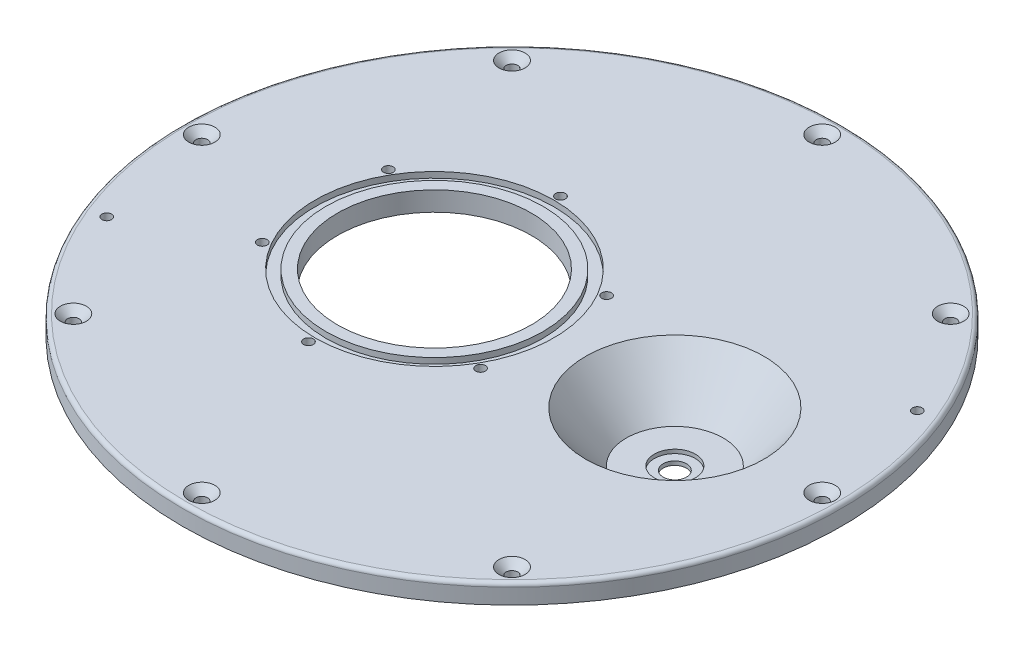
SolidWorks part; units mm, degrees
ref_plane "前视基准面" through (0, 0, 0) normal (0, 0, 1) x (1, 0, 0)
ref_plane "上视基准面" through (0, 0, 0) normal (0, 1, 0) x (1, 0, 0)
ref_plane "右视基准面" through (0, 0, 0) normal (1, 0, 0) x (0, 0, -1)
sketch "草图1" plane through (0, 0, 0) normal (0, 1, 0) x (1, 0, 0)
  circle A0 centre (0, 0) radius 85
  dimension "D1" = 170
extrude "凸台-拉伸1" add sketch "草图1" along normal blind 5
sketch "草图2" plane through (0, 5, 0) normal (0, 1, 0) x (1, 0, 0)
  circle A0 centre (0, 0) radius 80
  circle A1 centre (0, 80) radius 1.25
  circle A2 centre (0, 0) radius 80
  circle A3 centre (56.5685, 56.5685) radius 1.25
  circle A4 centre (0, 0) radius 80
  circle A5 centre (80, 0) radius 1.25
  circle A6 centre (0, 0) radius 80
  circle A7 centre (56.5685, -56.5685) radius 1.25
  circle A8 centre (0, 0) radius 80
  circle A9 centre (0, -80) radius 1.25
  circle A10 centre (0, 0) radius 80
  circle A11 centre (-56.5685, -56.5685) radius 1.25
  circle A12 centre (0, 0) radius 80
  circle A13 centre (-80, 0) radius 1.25
  circle A14 centre (0, 0) radius 80
  circle A15 centre (-56.5685, 56.5685) radius 1.25
  point P28 (0, 0)
  dimension "D1" = 160
  dimension "D2" = 2.5
  dimension "D3" = 8
hole_wizard "M3 螺纹孔1" positions "3D草图2" profile "草图17" tap size "M3" standard "ISO" end condition through all
sketch3d "3D草图2"
  point P0 (0, 5, -80)
  point P3 (56.5685, 5, -56.5685)
  point P6 (80, 5, 0)
  point P9 (56.5685, 5, 56.5685)
  point P12 (0, 5, 80)
  point P15 (-56.5685, 5, 56.5685)
  point P18 (-56.5685, 5, -56.5685)
  point P21 (-80, 5, 0)
sketch "草图17" plane through (0, 5, -80) normal (1, 0, 0) x (0, 0, 1)
  line L0 (0, 0) -> (0, 5)
  line L1 (0, 5) -> (1.5, 5)
  line L2 (1.5, 5) -> (1.5, 1.86)
  line L3 (1.5, 1.86) -> (3.36, 0)
  line L5 (3.36, 0) -> (0, 0)
  line L6 (-1.5, 1.86) -> (-3.36, 0) construction
  line L11 (0, -6.35) -> (0, 107.95) construction
  dimension "通孔螺纹孔钻头直径" = 3
  dimension "通孔螺纹孔钻头深度" = 5
  dimension "近端锥形沉头孔直径" = 6.72
  dimension "近端锥形沉头孔角度" = 90
cosmetic thread "孔螺蚊线18" parameters "D2"=3
cosmetic thread "孔螺蚊线19" parameters "D2"=3
cosmetic thread "孔螺蚊线20" parameters "D2"=3
cosmetic thread "孔螺蚊线21" parameters "D2"=3
cosmetic thread "孔螺蚊线22" parameters "D2"=3
cosmetic thread "孔螺蚊线23" parameters "D2"=3
cosmetic thread "孔螺蚊线24" parameters "D2"=3
cosmetic thread "孔螺蚊线25" parameters "D2"=3
sketch "草图3" plane through (0, 5, 0) normal (0, 1, 0) x (1, 0, 0)
  line L0 (0, 0) -> (42, 0)
  line L1 (0, 0) -> (-20, 0)
  circle A0 centre (-20, 0) radius 25
  circle A1 centre (42, 0) radius 23
  point P9 (-20, 0)
  dimension "D4" = 46
  dimension "D8" = 50
  dimension "D1" = 42
  dimension "D2" = 20
extrude "切除-拉伸2" cut sketch "草图3" against normal blind 5 contours A0 | A1
sketch "草图6" plane through (0, 0, 0) normal (0, 0, 1) x (1, 0, 0)
  line L0 (0, 5) -> (19, 5) construction
  line L1 (85, 5) -> (-85, 5) construction
  line L2 (19, 5) -> (29.5, -8)
  line L3 (0, 0) -> (19, 0) construction
  line L4 (-85, 0) -> (85, 0) construction
  line L5 (19, 0) -> (27.5, -10)
  line L6 (0, 5) -> (0, 0)
  line L7 (29.5, -8) -> (36.7, -8)
  line L8 (39, -10) -> (27.5, -10)
  line L9 (36.7, -8) -> (36.7, -9)
  line L10 (36.7, -9) -> (39, -9)
  line L11 (19, 0) -> (19, 5)
  line L12 (39, -10) -> (39, -9)
  line L13 (0, 0) -> (42, 0) construction
  line L14 (42, 0) -> (42, -17.7637)
  line L15 (39, -10) -> (42, -10)
  dimension "D1" = 19
  dimension "D2" = 10
  dimension "D3" = 19
  dimension "D4" = 1
  dimension "D5" = 11.5
  dimension "D6" = 3
  dimension "D7" = 7.2
  dimension "D8" = 1
  dimension "D9" = 2.3
  dimension "D10" = 42
revolve "旋转1" add sketch "草图6" angle 360 about L14
sketch "草图14" plane through (0, 5, 0) normal (0, 1, 0) x (1, 0, 0)
  circle A0 centre (-20, 0) radius 28
  circle A1 centre (-20, 0) radius 30.8
  dimension "D1" = 56
  dimension "D2" = 61.6
extrude "切除-拉伸5" cut sketch "草图14" against normal blind 1.5
fillet "圆角1" radius 1 1 edges at (0, 5, 85)
sketch "草图15" plane through (0, 5, 0) normal (0, 1, 0) x (1, 0, 0)
  circle A0 centre (-20, 0) radius 32.5
  circle A1 centre (-20, 32.5) radius 1.25
  circle A2 centre (8.1458, 16.25) radius 1.25
  circle A3 centre (8.1458, -16.25) radius 1.25
  circle A4 centre (-20, -32.5) radius 1.25
  circle A5 centre (-48.1458, -16.25) radius 1.25
  circle A6 centre (-48.1458, 16.25) radius 1.25
  point P18 (-20, 0)
  dimension "D1" = 65
  dimension "D2" = 2.5
  dimension "D3" = 6
hole_wizard "M2.5 螺纹孔3" positions "3D草图3" profile "草图18" tap size "M2.5" standard "ISO"
sketch3d "3D草图3"
  point P0 (-20, 5, -32.5)
  point P3 (8.1458, 5, -16.25)
  point P6 (8.1458, 5, 16.25)
  point P9 (-20, 5, 32.5)
  point P12 (-48.1458, 5, -16.25)
  point P15 (-48.1458, 5, 16.25)
sketch "草图18" plane through (-20, 5, -32.5) normal (1, 0, 0) x (0, 0, 1)
  line L0 (0, 0) -> (0, 3.7511)
  line L1 (0, 3.7511) -> (1.25, 3)
  line L2 (1.25, 3) -> (1.25, 0)
  line L5 (1.25, 0) -> (0, 0)
  line L10 (0, 3.7511) -> (-1.25, 3) construction
  line L11 (0, -6.35) -> (0, 107.95) construction
  dimension "螺纹孔钻头直径" = 2.5
  dimension "螺纹孔钻头深度" = 3
  dimension "导头角度" = 118
cosmetic thread "孔螺蚊线10" parameters "D1"=3, "D2"=2.5
cosmetic thread "孔螺蚊线11" parameters "D1"=3, "D2"=2.5
cosmetic thread "孔螺蚊线12" parameters "D1"=3, "D2"=2.5
cosmetic thread "孔螺蚊线13" parameters "D1"=3, "D2"=2.5
cosmetic thread "孔螺蚊线14" parameters "D1"=3, "D2"=2.5
cosmetic thread "孔螺蚊线15" parameters "D1"=3, "D2"=2.5
sketch "草图19" plane through (0, 5, 0) normal (0, 1, 0) x (1, 0, 0)
  line L0 (-73.9104, -30.6147) -> (73.9104, 30.6147)
  line L1 (0, 0) -> (135.9567, 0)
  point P4 (0, 0)
  dimension "D1" = 160
  dimension "D2" = 22.5
hole_wizard "M3 螺纹孔2" positions "3D草图4" profile "草图20" tap size "M3" standard "ISO" end condition through all
sketch3d "3D草图4"
  point P0 (-73.9104, 5, 30.6147)
  point P3 (73.9104, 5, -30.6147)
cosmetic thread "孔螺蚊线16" parameters "D2"=3
cosmetic thread "孔螺蚊线17" parameters "D2"=3
sketch "草图20" plane through (-73.9104, 5, 30.6147) normal (1, 0, 0) x (0, 0, 1)
  line L0 (0, 0) -> (0, 15)
  line L1 (0, 15) -> (1.25, 15)
  line L2 (1.25, 15) -> (1.25, 0)
  line L5 (1.25, 0) -> (0, 0)
  line L11 (0, -6.35) -> (0, 107.95) construction
  dimension "通孔螺纹孔钻头直径" = 2.5
  dimension "通孔螺纹孔钻头深度" = 15
